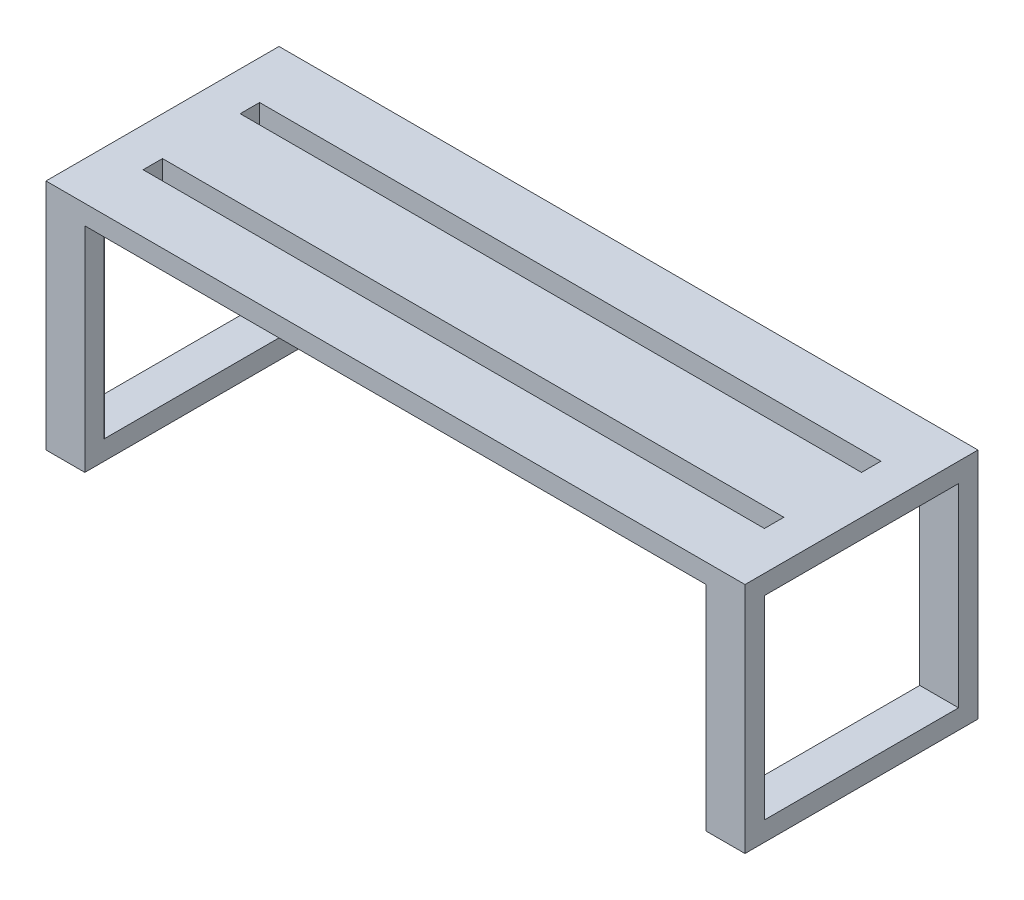
SolidWorks part; units mm, degrees
ref_plane "Alzado" through (0, 0, 0) normal (0, 0, 1) x (1, 0, 0)
ref_plane "Planta" through (0, 0, 0) normal (0, 1, 0) x (1, 0, 0)
ref_plane "Vista lateral" through (0, 0, 0) normal (1, 0, 0) x (0, 0, -1)
sketch "Croquis2" plane through (0, 0, 0) normal (1, 0, 0) x (0, 0, -1)
  line L0 (-30, 30.1305) -> (30, -29.8695) construction
  line L1 (-30, 30.1305) -> (30, 30.1305)
  line L2 (-30, 30.1305) -> (-30, -29.8695)
  line L3 (-30, -29.8695) -> (30, -29.8695)
  line L4 (30, 30.1305) -> (30, -29.8695)
  line L6 (-25, 25.1305) -> (25, 25.1305)
  line L7 (-25, 25.1305) -> (-25, -24.8695)
  line L8 (-25, -24.8695) -> (25, -24.8695)
  line L9 (25, 25.1305) -> (25, -24.8695)
  point P4 (0, -29.8695)
  point P11 (23.2428, -23.2428)
  dimension "D1" = 60
  dimension "D3" = 60
  dimension "D4" = 5
  dimension "D5" = 5
  dimension "D6" = 50
  dimension "D7" = 5
extrude "Saliente-Extruir1" add sketch "Croquis2" along normal blind 10
sketch "Croquis3" plane through (10, 0, 0) normal (1, 0, 0) x (0, 0, -1)
  line L0 (30, -29.8695) -> (30, 30.1305) construction
  line L1 (-30, 30.1305) -> (30, 30.1305)
  line L2 (-30, 30.1305) -> (-30, 25.1305)
  line L3 (-30, 25.1305) -> (30, 25.1305)
  line L4 (30, 30.1305) -> (30, 25.1305)
extrude "Saliente-Extruir2" add sketch "Croquis3" along normal blind 170
sketch "Croquis5" plane through (0, 25.1305, 0) normal (0, -1, 0) x (1, 0, 0)
  line L0 (180, -30) -> (10, -30) construction
  line L1 (180, 30) -> (170, 30)
  line L2 (180, 30) -> (180, -30)
  line L3 (180, -30) -> (170, -30)
  line L4 (170, 30) -> (170, -30)
extrude "Saliente-Extruir3" add sketch "Croquis5" along normal blind 55
sketch "Croquis7" plane through (180, 0, 0) normal (1, 0, 0) x (0, 0, -1)
  line L0 (30, 30.1305) -> (-30, 30.1305) construction
  line L1 (-25, 25.158) -> (25, 25.158)
  line L2 (-25, 25.158) -> (-25, -24.8695)
  line L3 (-25, -24.8695) -> (25, -24.8695)
  line L4 (25, 25.158) -> (25, -24.8695)
  line L5 (-30, 30.1305) -> (-30, -29.8695) construction
  line L6 (30, -29.8695) -> (30, 30.1305) construction
  line L7 (30, -29.8695) -> (-30, -29.8695) construction
  dimension "D1" = 4.9725
  dimension "D2" = 5
  dimension "D3" = 5
  dimension "D4" = 5
extrude "Cortar-Extruir1" cut sketch "Croquis7" against normal blind 10
sketch "Croquis8" plane through (0, 30.1305, 0) normal (0, 1, 0) x (1, 0, 0)
  line L0 (0, 30) -> (0, -30) construction
  line L1 (10, 15) -> (170, 15)
  line L2 (10, 15) -> (10, 10)
  line L3 (10, 10) -> (170, 10)
  line L4 (170, 15) -> (170, 10)
  line L5 (10, -10) -> (170, -10)
  line L6 (10, -10) -> (10, -15)
  line L7 (10, -15) -> (170, -15)
  line L8 (170, -10) -> (170, -15)
  line L9 (180, 30) -> (180, -30) construction
  line L12 (180, 30) -> (0, 30) construction
  line L13 (180, -30) -> (0, -30) construction
  point P10 (10, -12.5)
  dimension "D1" = 10
  dimension "D2" = 10
  dimension "D3" = 10
  dimension "D4" = 10
  dimension "D5" = 5
  dimension "D6" = 5
  dimension "D7" = 15
  dimension "D8" = 15
extrude "Cortar-Extruir2" cut sketch "Croquis8" against normal blind 10
